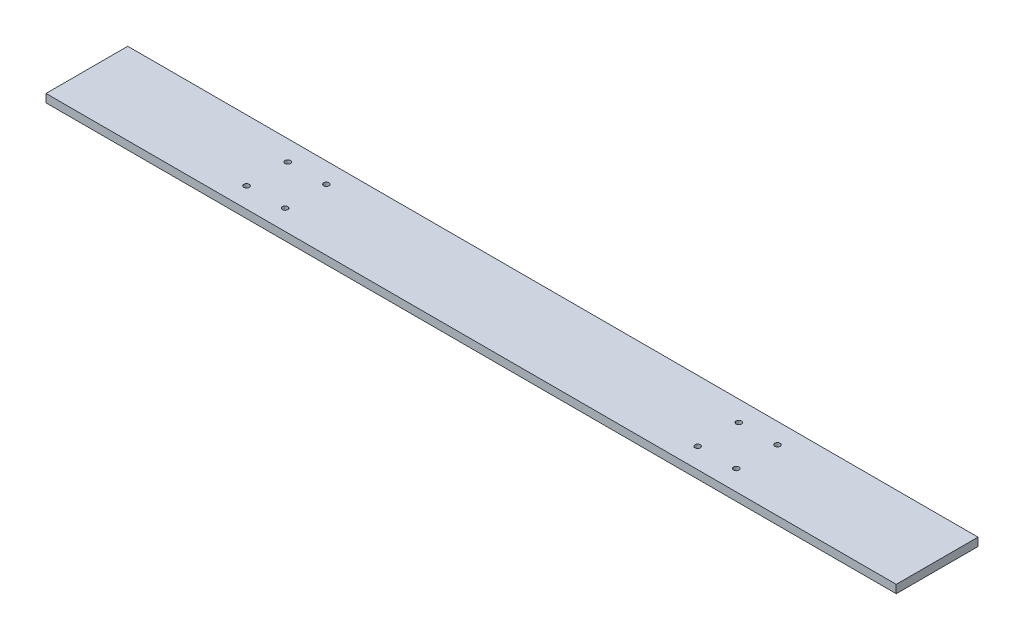
SolidWorks part; units mm, degrees
ref_plane "Front Plane" through (0, 0, 0) normal (0, 0, 1) x (1, 0, 0)
ref_plane "Top Plane" through (0, 0, 0) normal (0, 1, 0) x (1, 0, 0)
ref_plane "Right Plane" through (0, 0, 0) normal (1, 0, 0) x (0, 0, -1)
sketch "Sketch1" plane through (0, 0, 0) normal (0, 1, 0) x (1, 0, 0)
  line L1 (-4.8655, -0.9956) -> (655.5345, -0.9956)
  line L2 (-4.8655, -0.9956) -> (-4.8655, 62.5044)
  line L3 (-4.8655, 62.5044) -> (655.5345, 62.5044)
  line L4 (655.5345, -0.9956) -> (655.5345, 62.5044)
  line L5 (-4.8655, -0.9956) -> (655.5345, 62.5044) construction
  line L6 (-4.8655, 62.5044) -> (655.5345, -0.9956) construction
  point P0 (325.3345, 30.7544)
  dimension "D1" = 660.4
  dimension "D2" = 63.5
extrude "Boss-Extrude1" add sketch "Sketch1" along normal blind 6.35
sketch "Sketch2" plane through (0, 6.35, 0) normal (0, 1, 0) x (1, 0, 0)
  line L0 (655.5345, -0.9956) -> (655.5345, 62.5044) construction
  line L1 (655.5345, 62.5044) -> (-4.8655, 62.5044) construction
  line L2 (-4.8655, -0.9956) -> (655.5345, -0.9956) construction
  line L3 (-4.8655, 62.5044) -> (-4.8655, -0.9956) construction
  circle A0 centre (515.5345, 46.7544) radius 2.1
  circle A1 centre (515.5345, 14.7544) radius 2.1
  circle A2 centre (485.5345, 46.7544) radius 2.1
  circle A3 centre (485.5345, 14.7544) radius 2.1
  circle A4 centre (165.1345, 46.7544) radius 2.1
  circle A5 centre (165.1345, 14.7544) radius 2.1
  circle A6 centre (135.1345, 46.7544) radius 2.1
  circle A7 centre (135.1345, 14.7544) radius 2.1
  dimension "D1" = 4.2
  dimension "D3" = 30
  dimension "D4" = 32
  dimension "D5" = 15.75
  dimension "D6" = 15.75
  dimension "D7" = 4.2
  dimension "D10" = 140
  dimension "D11" = 140
  dimension "D8" = 30
  dimension "D9" = 32
extrude "Cut-Extrude1" cut sketch "Sketch2" against normal through all
